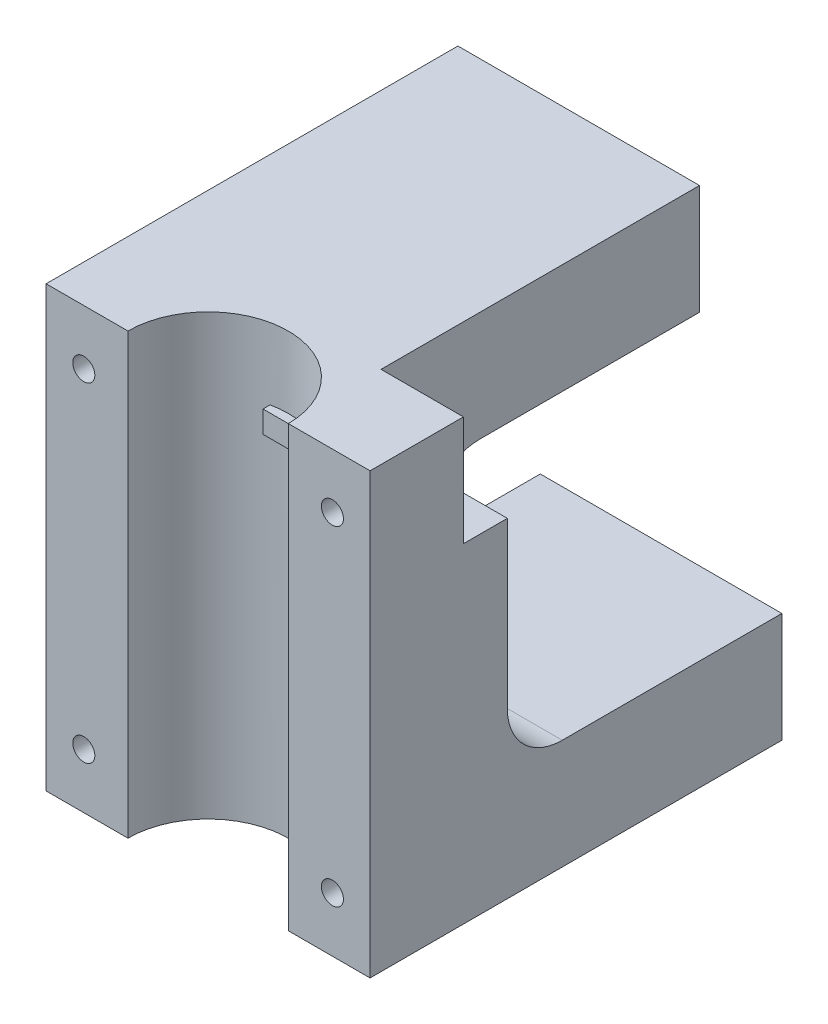
SolidWorks part; units mm, degrees
ref_plane "Front Plane" through (0, 0, 0) normal (0, 0, 1) x (1, 0, 0)
ref_plane "Top Plane" through (0, 0, 0) normal (0, 1, 0) x (1, 0, 0)
ref_plane "Right Plane" through (0, 0, 0) normal (1, 0, 0) x (0, 0, -1)
sketch "Sketch1" plane through (0, 0, 0) normal (0, 0, 1) x (1, 0, 0)
  line L6 (-37.465, -50.8) -> (37.465, -50.8)
  line L7 (-37.465, -50.8) -> (-37.465, 50.8)
  line L8 (-37.465, 50.8) -> (37.465, 50.8)
  line L9 (37.465, -50.8) -> (37.465, 50.8)
  line L10 (-37.465, -50.8) -> (37.465, 50.8) construction
  line L11 (-37.465, 50.8) -> (37.465, -50.8) construction
  point P0 (0, 0)
  dimension "D1" = 74.93
  dimension "D2" = 101.6
extrude "Boss-Extrude2" add sketch "Sketch1" against normal blind 95.25
sketch "Sketch2" plane through (0, 50.8, 0) normal (0, 1, 0) x (1, 0, 0)
  line L0 (37.465, 0) -> (-37.465, 0) construction
  arc A0 (-18.542, 0) -> (18.542, 0) centre (0, 0) cw
  point P7 (0, 18.542)
  dimension "D1" = 18.542
extrude "Cut-Extrude2" cut sketch "Sketch2" against normal through all and the other way through all flip side to cut
ref_plane "Plane1" through (0, 31.75, 0) normal (0, 1, 0) x (1, 0, 0)
sketch "Sketch4" plane through (0, 31.75, 0) normal (0, 1, 0) x (1, 0, 0)
  line L0 (3.81, 16.51) -> (3.81, 95.25)
  line L1 (37.465, 95.25) -> (-37.465, 95.25) construction
  line L2 (3.81, 95.25) -> (-3.81, 95.25)
  line L3 (-3.81, 95.25) -> (-3.81, 16.51)
  line L4 (-3.81, 16.51) -> (3.81, 16.51)
  arc A2 (18.542, 0) -> (-18.542, 0) centre (0, 0) ccw construction
  point P3 (0, 95.25)
  point P5 (0, 18.542)
  dimension "D2" = 2.032
  dimension "D1" = 7.62
extrude "Boss-Extrude3" add sketch "Sketch4" along normal mid plane 5.08
hole_wizard "Tap Drill for 1/4-20 Tap1" positions "Sketch6" profile "Sketch7" hole size "1/4-20" standard "ANSI Inch" end condition through all
sketch "Sketch6" plane through (0, 0, 0) normal (0, 0, 1) x (1, 0, 0)
  line L0 (-37.465, 50.8) -> (-37.465, -50.8) construction
  line L3 (-18.542, 50.8) -> (-37.465, 50.8) construction
  line L4 (37.465, -50.8) -> (37.465, 50.8) construction
  line L7 (-37.465, -50.8) -> (-18.542, -50.8) construction
  point P0 (-28.7528, 38.1)
  point P2 (28.7528, 38.1)
  point P4 (-28.7528, -38.1)
  point P6 (28.7528, -38.1)
  point P33 (0, 0)
  dimension "D1" = 8.7122
  dimension "D2" = 12.7
  dimension "D3" = 8.7122
  dimension "D4" = 12.7
sketch "Sketch7" plane through (-28.7528, 38.1, 0) normal (1, 0, 0) x (0, -1, 0)
  line L0 (0, 0) -> (0, 95.25)
  line L1 (0, 95.25) -> (2.5527, 95.25)
  line L2 (2.5527, 95.25) -> (2.5527, 0)
  line L5 (2.5527, 0) -> (0, 0)
  line L11 (0, -6.35) -> (0, 107.95) construction
  dimension "Thru Hole Dia." = 5.1054
  dimension "Thru Hole Depth" = 95.25
sketch "Sketch9" plane through (0, 0, -95.25) normal (0, 0, -1) x (-1, 0, 0)
  line L0 (-37.465, 25.4) -> (-18.415, 25.4)
  line L1 (-37.465, -50.8) -> (-37.465, 50.8) construction
  line L2 (-18.415, 25.4) -> (-18.415, 50.8)
  line L3 (-37.465, 50.8) -> (37.465, 50.8) construction
  line L4 (-18.415, 50.8) -> (-37.465, 50.8)
  line L5 (-37.465, 50.8) -> (-37.465, 25.4)
  line L8 (37.465, 50.8) -> (37.465, -50.8) construction
  line L13 (37.465, -50.8) -> (-37.465, -50.8) construction
  line L17 (37.465, -25.4) -> (18.415, -25.4)
  line L18 (18.415, -25.4) -> (18.415, -50.8)
  line L19 (18.415, -50.8) -> (37.465, -50.8)
  line L20 (37.465, -50.8) -> (37.465, -25.4)
  point P4 (-21.7662, 29.5857)
  dimension "D1" = 25.4
  dimension "D2" = 25.4
  dimension "D3" = 19.05
  dimension "D4" = 19.05
extrude "Cut-Extrude3" cut sketch "Sketch9" against normal blind 73.66 contours L5 L0 L2 L4 | L20 L17 L18 L19
sketch "Sketch10" plane through (0, 0, -95.25) normal (0, 0, -1) x (-1, 0, 0)
  line L1 (37.465, -25.4) -> (-37.465, -25.4)
  line L2 (37.465, -25.4) -> (37.465, 25.4)
  line L3 (37.465, 25.4) -> (-37.465, 25.4)
  line L4 (-37.465, -25.4) -> (-37.465, 25.4)
  line L5 (37.465, -25.4) -> (-37.465, 25.4) construction
  line L6 (37.465, 25.4) -> (-37.465, -25.4) construction
  point P0 (0, 0)
extrude "Cut-Extrude4" cut sketch "Sketch10" against normal blind 63.5
fillet "Fillet1" radius 12.7 2 edges at (9.525, -25.4, -31.75) (-9.525, 25.4, -31.75)
